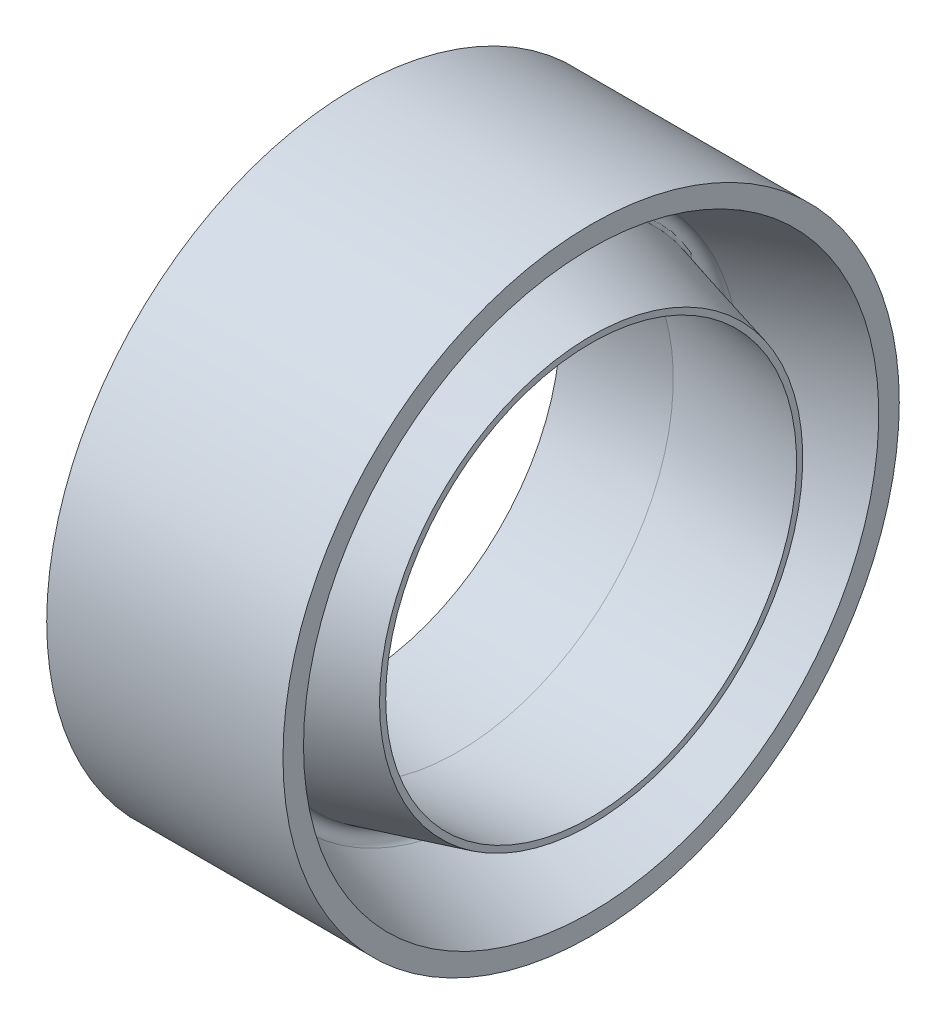
SolidWorks part; units mm, degrees
ref_plane "Płaszczyzna przednia" through (0, 0, 0) normal (0, 0, 1) x (1, 0, 0)
ref_plane "Płaszczyzna górna" through (0, 0, 0) normal (0, 1, 0) x (1, 0, 0)
ref_plane "Płaszczyzna prawa" through (0, 0, 0) normal (1, 0, 0) x (0, 0, -1)
sketch "Szkic1" plane through (0, 0, 0) normal (0, 0, 1) x (1, 0, 0)
  line L0 (-30.5, 15.3425) -> (-42, 15.3425)
  line L2 (-42, 15.3425) -> (-42, -14.6575) construction
  line L3 (-42, 15.3425) -> (-42, 11.8425)
  line L4 (-42, 11.8425) -> (-39.3515, 11.8425)
  line L5 (-39.3164, 11.6489) -> (-42, 10.6425)
  line L6 (-42, 10.6425) -> (-42, 10.3425)
  line L7 (-42, 10.3425) -> (-37, 10.8425)
  line L8 (-37, 10.8425) -> (-30.5, 10.3425)
  line L10 (-30.5, 10.3425) -> (-30.5, 10.6425)
  line L11 (-30.5, 10.6425) -> (-35.6397, 11.9867)
  line L12 (-35.6561, 12.756) -> (-30.5, 14.3425)
  line L13 (-30.5, 14.3425) -> (-30.5, 15.3425)
  line L15 (-61.484, 0.3425) -> (-32.9719, 0.3425) construction
  arc A0 (-35.6397, 11.9867) -> (-35.6561, 12.756) centre (-35.5384, 12.3737) cw
  arc A2 (-39.3515, 11.8425) -> (-39.3164, 11.6489) centre (-39.3515, 11.7425) cw
  point P20 (-37, 12.3425)
  point P23 (-30.5, 14.3425)
  point P26 (-38.8, 11.8425)
  dimension "D2" = 0.4
  dimension "D3" = 1
  dimension "D5" = 0.1
  dimension "D4" = 3.2
  dimension "D6" = 3.5
  dimension "D7" = 20
  dimension "D8" = 5
  dimension "D9" = 0.5
  dimension "D10" = 5
  dimension "D11" = 3
  dimension "D12" = 0.3
  dimension "D13" = 11.5
  dimension "D14" = 6.5
revolve "Obrót1" add sketch "Szkic1" angle 360 about L15
